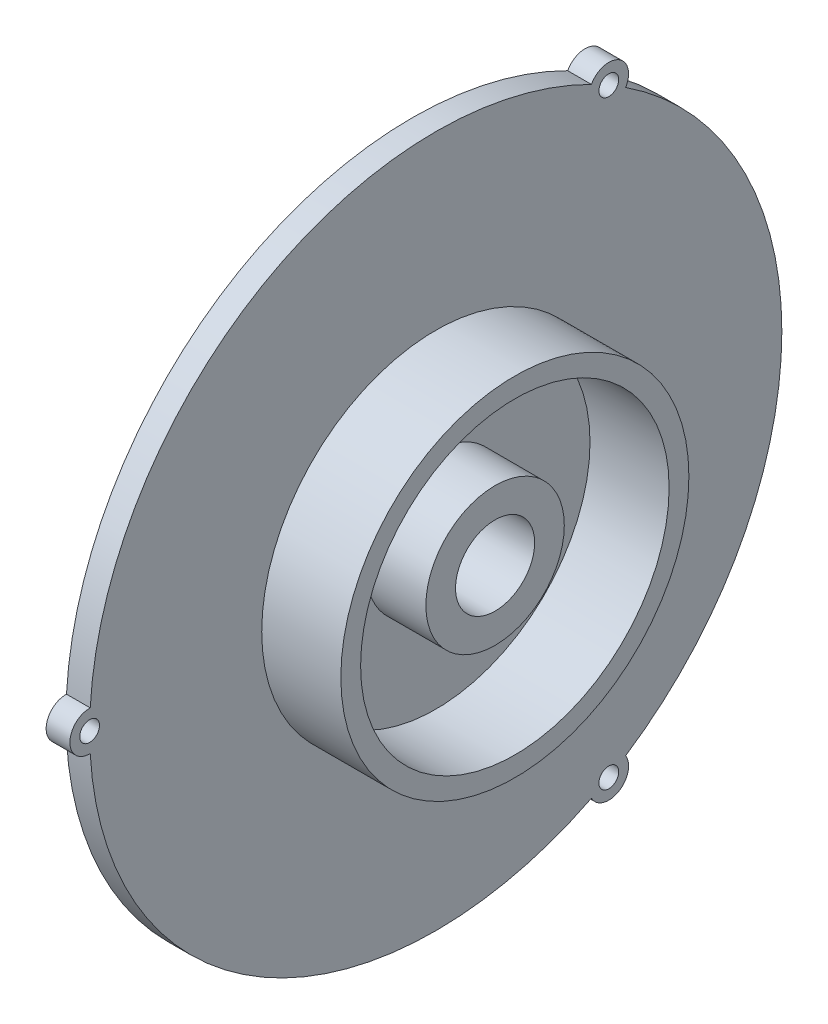
SolidWorks part; units mm, degrees
ref_plane "Front Plane" through (0, 0, 0) normal (1, 0, 0) x (0, 1, 0)
ref_plane "Top Plane" through (0, 0, 0) normal (0, 0, 1) x (0, 1, 0)
ref_plane "Right Plane" through (0, 0, 0) normal (0, 1, 0) x (-1, 0, 0)
sketch "Sketch1" plane through (0, 0, 0) normal (0, 1, 0) x (-1, 0, 0)
  line L0 (0, 0) -> (0, 87.5)
  line L6 (6, 87.5) -> (6, 0)
  line L9 (-38.1109, 0) -> (43.1075, 0) construction
  line L10 (6, 0) -> (0, 0)
  line L14 (6, 87.5) -> (0, 87.5)
  dimension "D1" = 87.5
  dimension "D2" = 6
revolve "Revolve1" add sketch "Sketch1" angle 360 about L9
sketch "Sketch3" plane through (0, 0, 0) normal (1, 0, 0) x (0, 1, 0)
  circle A0 centre (0, 0) radius 8
  dimension "D1" = 16
extrude "Cut-Extrude2" cut sketch "Sketch3" against normal blind 30
sketch "Sketch4" plane through (-6, 0, 0) normal (-1, 0, 0) x (0, -1, 0)
  circle A0 centre (0, 87.5) radius 5
  circle A1 centre (0, 0) radius 87.5 construction
  dimension "D1" = 10
extrude "Boss-Extrude1" add sketch "Sketch4" against normal blind 6
sketch "Sketch6" plane through (-6, 0, 0) normal (-1, 0, 0) x (0, -1, 0)
  circle A0 centre (0, 87.5) radius 2.5
  dimension "D1" = 5
pattern_circular "CirPattern2" count 3 every 120 about axis through (0, 0, 0) along (1, 0, 0) of "Boss-Extrude1"
extrude "Cut-Extrude3" cut sketch "Sketch6" against normal blind 6
pattern_circular "CirPattern3" count 3 every 120 about axis through (0, 0, 0) along (1, 0, 0) of "Cut-Extrude3"
sketch "Sketch8" plane through (0, 0, 0) normal (1, 0, 0) x (0, 1, 0)
  circle A0 centre (0, 0) radius 17.5
  circle A3 centre (0, 0) radius 10
  dimension "D1" = 35
  dimension "D2" = 20
extrude "Boss-Extrude2" add sketch "Sketch8" along normal blind 15
sketch "Sketch10" plane through (0, 0, 0) normal (1, 0, 0) x (0, 1, 0)
  circle A0 centre (0, 0) radius 39
  circle A1 centre (0, 0) radius 44
  dimension "D1" = 78
  dimension "D2" = 88
extrude "Boss-Extrude3" add sketch "Sketch10" along normal blind 20
sketch "Sketch11" plane through (-6, 0, 0) normal (-1, 0, 0) x (0, -1, 0)
  circle A0 centre (0, 0) radius 81.5
extrude "Cut-Extrude4" cut sketch "Sketch11" against normal blind 3
sketch "Sketch12" plane through (-3, 0, 0) normal (-1, 0, 0) x (0, -1, 0)
  circle A0 centre (0, 0) radius 15
  circle A1 centre (0, 0) radius 8
  circle A2 centre (0, 0) radius 8 construction
  dimension "D2" = 30
extrude "Boss-Extrude4" add sketch "Sketch12" along normal up to surface (3 mm away)
